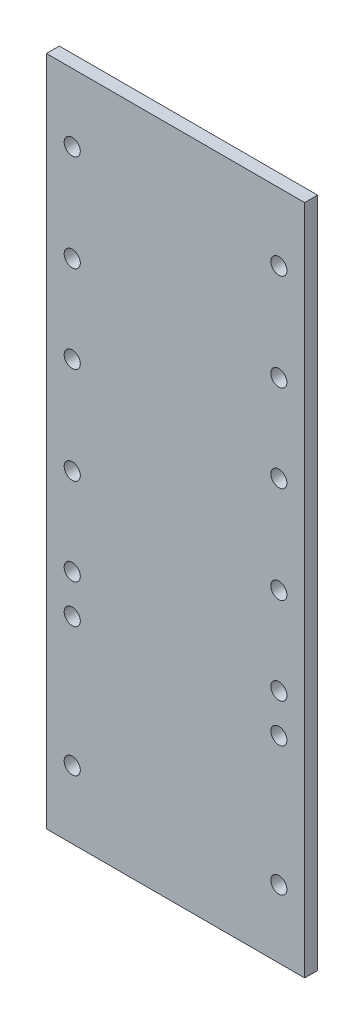
SolidWorks part; units mm, degrees
ref_plane "Plano frontal" through (0, 0, 0) normal (0, 0, 1) x (1, 0, 0)
ref_plane "Plano superior" through (0, 0, 0) normal (0, 1, 0) x (1, 0, 0)
ref_plane "Plano direito" through (0, 0, 0) normal (1, 0, 0) x (0, 0, -1)
sketch "Esboço1" plane through (0, 0, 0) normal (0, 0, 1) x (1, 0, 0)
  line L1 (17.9082, 16.2491) -> (97.9082, 16.2491)
  line L2 (17.9082, 16.2491) -> (17.9082, -191.7509)
  line L3 (17.9082, -191.7509) -> (97.9082, -191.7509)
  line L4 (97.9082, 16.2491) -> (97.9082, -191.7509)
  circle A0 centre (25.9082, -4.7509) radius 2.5
  circle A1 centre (89.9082, -4.7509) radius 2.5
  circle A2 centre (89.9082, -170.7509) radius 2.5
  circle A3 centre (25.9082, -170.7509) radius 2.5
  circle A4 centre (89.9082, -130.7509) radius 2.5
  circle A5 centre (25.9082, -130.7509) radius 2.5
  circle A6 centre (89.9082, -118.7509) radius 2.5
  circle A7 centre (25.9082, -118.7509) radius 2.5
  circle A8 centre (89.9082, -61.7509) radius 2.5
  circle A9 centre (25.9082, -61.7509) radius 2.5
  circle A10 centre (89.9082, -34.7509) radius 2.5
  circle A11 centre (25.9082, -34.7509) radius 2.5
  circle A12 centre (89.9082, -91.7509) radius 2.5
  circle A13 centre (25.9082, -91.7509) radius 2.5
  dimension "D3" = 5
  dimension "D10" = 30
  dimension "D1" = 80
  dimension "D2" = 208
  dimension "D4" = 21
  dimension "D5" = 8
  dimension "D7" = 8
  dimension "D8" = 21
  dimension "D11" = 27
  dimension "D12" = 40
  dimension "D13" = 30
  dimension "D14" = 27
extrude "Ressalto-extrusão1" add sketch "Esboço1" along normal blind 4
